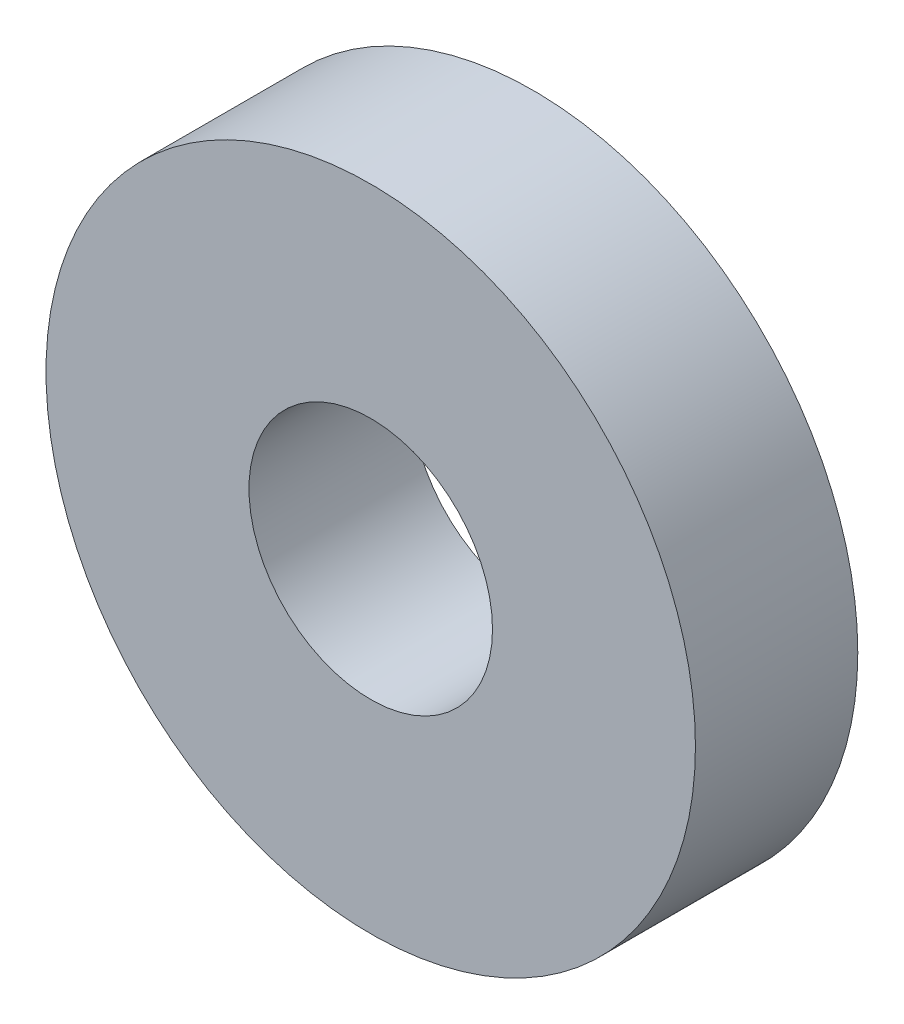
SolidWorks part; units mm, degrees
ref_plane "Front Plane" through (0, 0, 0) normal (0, 0, 1) x (1, 0, 0)
ref_plane "Top Plane" through (0, 0, 0) normal (0, 1, 0) x (1, 0, 0)
ref_plane "Right Plane" through (0, 0, 0) normal (1, 0, 0) x (0, 0, -1)
sketch "Sketch1" plane through (0, 0, 0) normal (0, 0, 1) x (1, 0, 0)
  circle A0 centre (0, 0) radius 2.3813
  circle A1 centre (0, 0) radius 6.35
  dimension "D1" = 12.7
  dimension "D2" = 4.7625
extrude "Boss-Extrude1" add sketch "Sketch1" along normal blind 3.175
